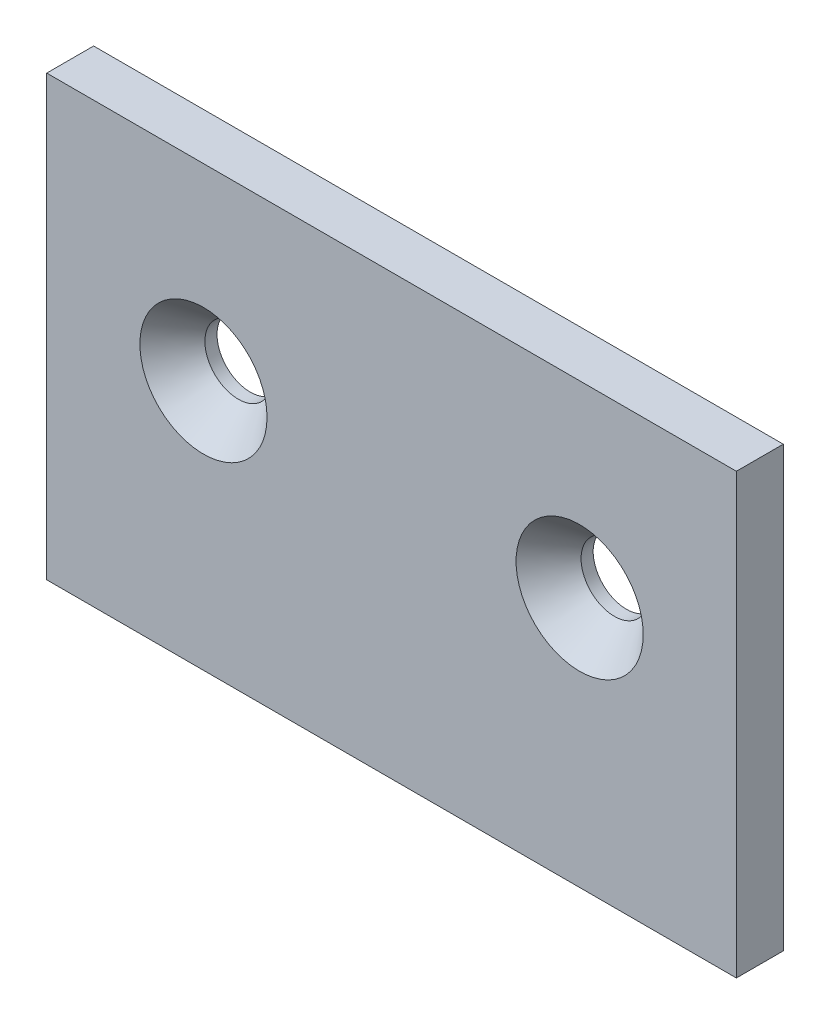
SolidWorks part; units mm, degrees
ref_plane "Front Plane" through (0, 0, 0) normal (0, 0, 1) x (1, 0, 0)
ref_plane "Top Plane" through (0, 0, 0) normal (0, 1, 0) x (1, 0, 0)
ref_plane "Right Plane" through (0, 0, 0) normal (1, 0, 0) x (0, 0, -1)
sketch "Sketch2" plane through (0, 0, 0) normal (0, 0, 1) x (1, 0, 0)
  line L1 (-34.925, 44.45) -> (34.925, 44.45)
  line L2 (-34.925, 44.45) -> (-34.925, 0)
  line L3 (-34.925, 0) -> (34.925, 0)
  line L4 (34.925, 44.45) -> (34.925, 0)
  point P4 (0, 0)
  dimension "D1" = 69.85
  dimension "D2" = 44.45
extrude "Boss-Extrude1" add sketch "Sketch2" against normal blind 4.7498 contours L1 L4 L3 L2
hole_wizard "CSK for 1/4 Flat Head Machine Screw5" positions "Sketch13" profile "Sketch14" countersink size "1/4" standard "ANSI Inch" end condition through all
sketch "Sketch13" plane through (0, 0, 0) normal (0, 0, 1) x (1, 0, 0)
  point P0 (-19.05, 25.4)
  point P3 (19.05, 25.4)
sketch "Sketch14" plane through (-19.05, 25.4, 0) normal (1, 0, 0) x (0, -1, 0)
  line L0 (0, 0) -> (0, 4.7498)
  line L1 (0, 4.7498) -> (3.3782, 4.7498)
  line L2 (3.3782, 4.7498) -> (3.3782, 3.5209)
  line L3 (3.3782, 3.5209) -> (6.4389, 0)
  line L5 (6.4389, 0) -> (0, 0)
  line L6 (-3.3782, 3.5209) -> (-6.4389, 0) construction
  line L11 (0, -6.35) -> (0, 107.95) construction
  dimension "Thru Hole Dia." = 6.7564
  dimension "Thru Hole Depth" = 4.7498
  dimension "Near C'Sink Dia." = 12.8778
  dimension "Near C'Sink Angle" = 82
